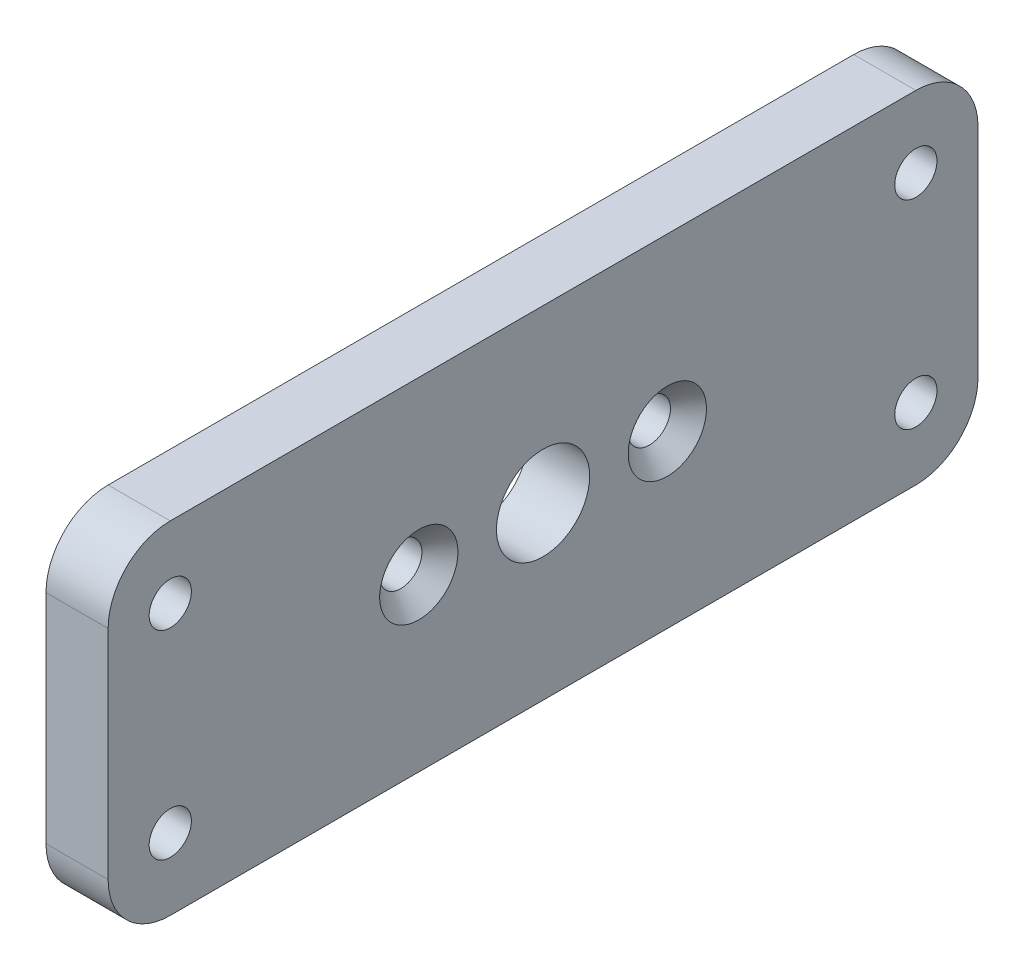
SolidWorks part; units mm, degrees
ref_plane "Front Plane" through (0, 0, 0) normal (0, 0, 1) x (1, 0, 0)
ref_plane "Top Plane" through (0, 0, 0) normal (0, 1, 0) x (1, 0, 0)
ref_plane "Right Plane" through (0, 0, 0) normal (1, 0, 0) x (0, 0, -1)
sketch "Sketch1" plane through (0, 0, 0) normal (1, 0, 0) x (0, 0, -1)
  line L0 (-30, -13.75) -> (30, -13.75)
  line L1 (-35, -8.75) -> (-35, 8.75)
  line L2 (35, -8.75) -> (35, 8.75)
  line L3 (-30, 13.75) -> (30, 13.75)
  line L4 (-35, -13.75) -> (35, 13.75) construction
  line L5 (35, -13.75) -> (-35, 13.75) construction
  arc A0 (-35, 8.75) -> (-30, 13.75) centre (-30, 8.75) cw
  arc A1 (-35, -8.75) -> (-30, -13.75) centre (-30, -8.75) ccw
  arc A2 (30, -13.75) -> (35, -8.75) centre (30, -8.75) ccw
  arc A3 (35, 8.75) -> (30, 13.75) centre (30, 8.75) ccw
  circle A4 centre (0, 0) radius 3.75
  point P1 (0, 0)
  dimension "D3" = 5
  dimension "D4" = 7.5
  dimension "D1" = 27.5
  dimension "D2" = 70
extrude "Boss-Extrude1" add sketch "Sketch1" along normal blind 5
sketch "Sketch2" plane through (5, 0, 0) normal (1, 0, 0) x (0, 0, -1)
  line L0 (-35, 0) -> (35, 0) construction
  line L1 (-35, 8.75) -> (-35, -8.75) construction
  line L2 (35, -8.75) -> (35, 8.75) construction
  line L3 (-30, 13.75) -> (-30, -13.75) construction
  line L4 (30, 13.75) -> (-30, 13.75) construction
  line L5 (-30, -13.75) -> (30, -13.75) construction
  line L6 (30, 13.75) -> (30, -13.75) construction
  point P6 (10, 0)
  point P7 (-10, 0)
  point P8 (-30, 0)
  point P10 (30, 0)
  point P19 (-30, 8)
  point P20 (30, 8)
  point P21 (30, -8)
  point P22 (-30, -8)
  dimension "D1" = 10
  dimension "D2" = 10
  dimension "D3" = 20
  dimension "D4" = 20
  dimension "D5" = 8
  dimension "D6" = 8
hole_wizard "CSK for M3 Countersunk Flat Head Screw1" positions "3DSketch3" profile "Sketch5" countersink size "M3" standard "ISO" end condition through all
sketch3d "3DSketch3"
  point P0 (5, 0, 10)
  point P3 (5, 0, -10)
sketch "Sketch5" plane through (5, 0, 10) normal (0, 1, 0) x (0, 0, -1)
  line L0 (0, 0) -> (0, 5)
  line L1 (0, 5) -> (1.7, 5)
  line L2 (1.7, 5) -> (1.7, 1.45)
  line L3 (1.7, 1.45) -> (3.15, 0)
  line L5 (3.15, 0) -> (0, 0)
  line L6 (-1.7, 1.45) -> (-3.15, 0) construction
  line L11 (0, -6.35) -> (0, 107.95) construction
  dimension "Thru Hole Dia." = 3.4
  dimension "Thru Hole Depth" = 5
  dimension "Near C'Sink Dia." = 6.3
  dimension "Near C'Sink Angle" = 90
sketch "Sketch7" plane through (0, 0, 0) normal (-1, 0, 0) x (0, 0, 1)
  point P0 (-30, 8)
  point P1 (-30, -8)
  point P3 (30, -8)
  point P5 (30, 8)
hole_wizard "M3 Clearance Hole3" positions "3DSketch5" profile "Sketch8" hole size "M3" standard "ISO"
sketch3d "3DSketch5"
  point P0 (0, 8, 30)
  point P2 (0, -8, 30)
  point P4 (0, -8, -30)
  point P6 (0, 8, -30)
sketch "Sketch8" plane through (0, 8, 30) normal (0, 1, 0) x (0, 0, 1)
  line L0 (0, 0) -> (0, 6.0215)
  line L1 (0, 6.0215) -> (1.7, 5)
  line L2 (1.7, 5) -> (1.7, 0)
  line L5 (1.7, 0) -> (0, 0)
  line L10 (0, 6.0215) -> (-1.7, 5) construction
  line L11 (0, -6.35) -> (0, 107.95) construction
  dimension "Hole Dia." = 3.4
  dimension "Hole Depth" = 5
  dimension "Drill Angle" = 118
